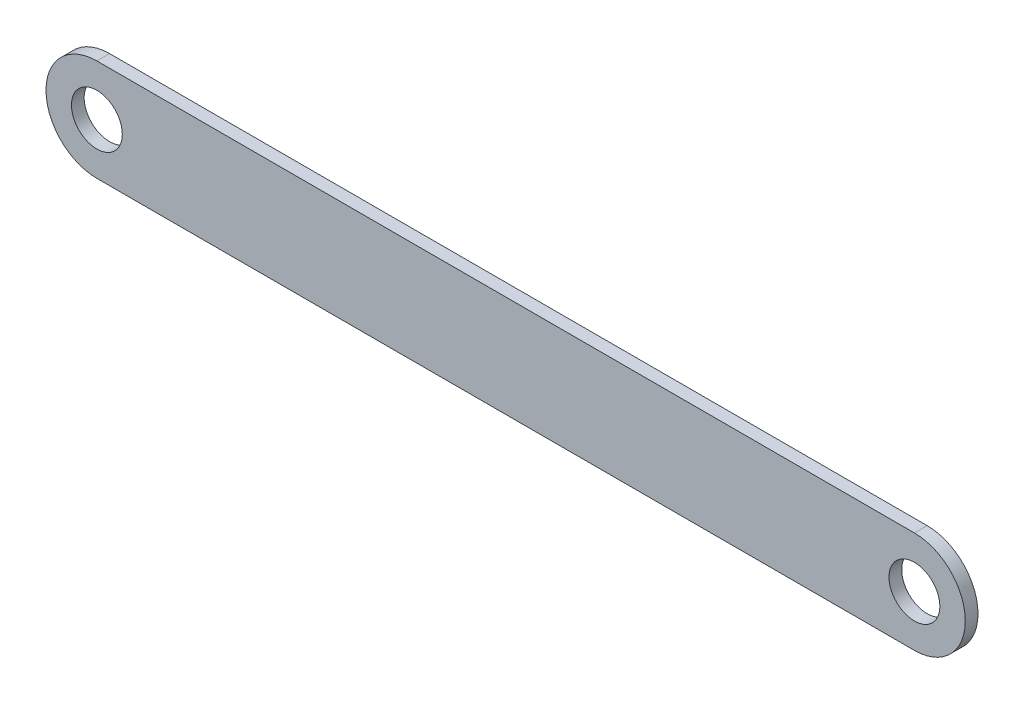
SolidWorks part; units mm, degrees
ref_plane "前视基准面" through (0, 0, 0) normal (0, 0, 1) x (1, 0, 0)
ref_plane "上视基准面" through (0, 0, 0) normal (0, 1, 0) x (1, 0, 0)
ref_plane "右视基准面" through (0, 0, 0) normal (1, 0, 0) x (0, 0, -1)
sketch "草图1" plane through (0, 0, 0) normal (0, 0, 1) x (1, 0, 0)
  line L0 (0, 0) -> (321.5174, 0) construction
  line L1 (0, 20) -> (321.5174, 20)
  line L2 (0, -20) -> (321.5174, -20)
  arc A0 (0, 20) -> (0, -20) centre (0, 0) ccw
  arc A1 (321.5174, -20) -> (321.5174, 20) centre (321.5174, 0) ccw
  circle A2 centre (0, 0) radius 10
  circle A3 centre (321.5174, 0) radius 10
  point P3 (160.7587, 0)
  dimension "D2" = 20
  dimension "D3" = 20
  dimension "D4" = 20
  dimension "D1" = 321.5174
extrude "凸台-拉伸1" add sketch "草图1" along normal blind 5
